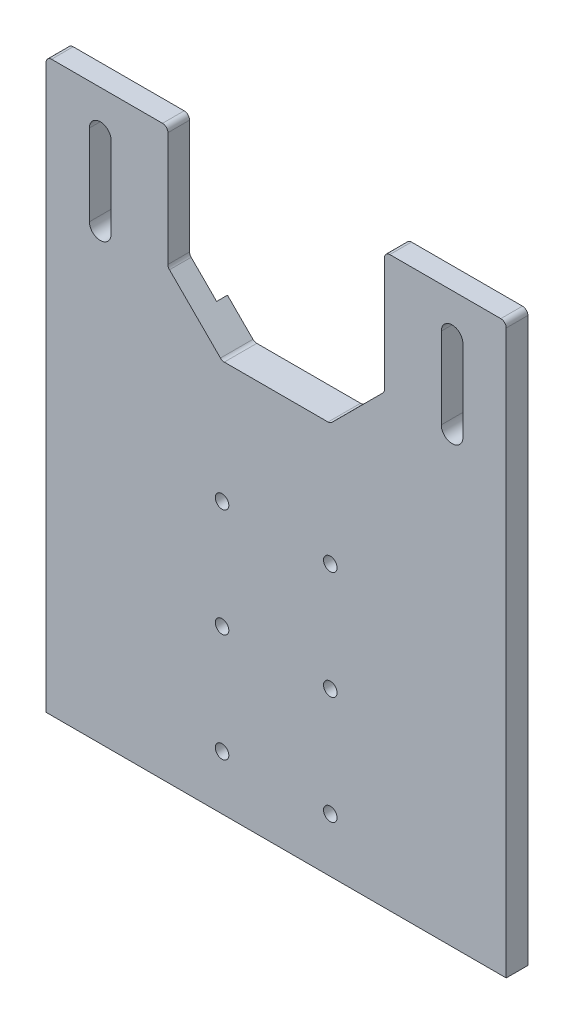
SolidWorks part; units mm, degrees
ref_plane "Front Plane" through (0, 0, 0) normal (0, 0, 1) x (1, 0, 0)
ref_plane "Top Plane" through (0, 0, 0) normal (0, 1, 0) x (1, 0, 0)
ref_plane "Right Plane" through (0, 0, 0) normal (1, 0, 0) x (0, 0, -1)
sketch "Sketch1" plane through (0, 0, 0) normal (0, 0, 1) x (1, 0, 0)
  line L22 (85, 223.351) -> (85, 0) construction
  line L23 (0, 210) -> (45, 210)
  line L24 (0, 210) -> (0, 0)
  line L25 (0, 0) -> (170, 0)
  line L26 (170, 210) -> (170, 0)
  line L27 (105, 145) -> (65, 145)
  line L28 (65, 145) -> (45, 165)
  line L29 (45, 165) -> (45, 210)
  line L30 (125, 165) -> (125, 210)
  line L31 (105, 145) -> (125, 165)
  line L32 (125, 210) -> (170, 210)
  line L33 (125, 210) -> (45, 210) construction
  line L34 (65, 0) -> (65, 210) construction
  line L35 (150, 195) -> (150, 165) construction
  line L36 (154, 195) -> (154, 165)
  line L37 (146, 195) -> (146, 165)
  line L38 (20, 195) -> (20, 165) construction
  line L39 (16, 195) -> (16, 165)
  line L40 (24, 195) -> (24, 165)
  circle A10 centre (65, 20) radius 2.5
  circle A11 centre (65, 60) radius 2.5
  circle A12 centre (65, 100) radius 2.5
  circle A13 centre (105, 100) radius 2.5
  circle A14 centre (105, 60) radius 2.5
  circle A15 centre (105, 20) radius 2.5
  arc A16 (154, 195) -> (146, 195) centre (150, 195) ccw
  arc A17 (146, 165) -> (154, 165) centre (150, 165) ccw
  arc A18 (16, 195) -> (24, 195) centre (20, 195) cw
  arc A19 (24, 165) -> (16, 165) centre (20, 165) cw
  point P59 (85, 145)
  point P63 (150, 180)
  point P82 (20, 180)
  dimension "D21" = 5
  dimension "D18" = 210
  dimension "D19" = 170
  dimension "D20" = 135
  dimension "D22" = 20
  dimension "D24" = 40
  dimension "D25" = 40
  dimension "D26" = 45
  dimension "D27" = 30
  dimension "D28" = 15
  dimension "D29" = 8
  dimension "D30" = 20
  dimension "D31" = 65
  dimension "D23" = 3
extrude "Boss-Extrude1" add sketch "Sketch1" along normal blind 12
sketch "Sketch3" plane through (0, 0, 0) normal (0, 0, -1) x (-1, 0, 0)
  line L0 (-45, 210) -> (0, 210) construction
  line L1 (0, 0) -> (-55, 0)
  line L2 (0, 0) -> (0, 210)
  line L3 (0, 210) -> (-55, 210)
  line L4 (-55, 0) -> (-55, 210)
  line L5 (-170, 0) -> (-115, 0)
  line L6 (-170, 0) -> (-170, 210)
  line L7 (-170, 210) -> (-115, 210)
  line L8 (-115, 0) -> (-115, 210)
  dimension "D1" = 60
extrude "Cut-Extrude1" cut sketch "Sketch3" against normal blind 4
fillet "Fillet1" radius 2 8 edges at (170, 210, 8) (125, 210, 8) (125, 165, 8) (105, 145, 6) (65, 145, 6) (45, 165, 8) (45, 210, 8) (0, 210, 8)
